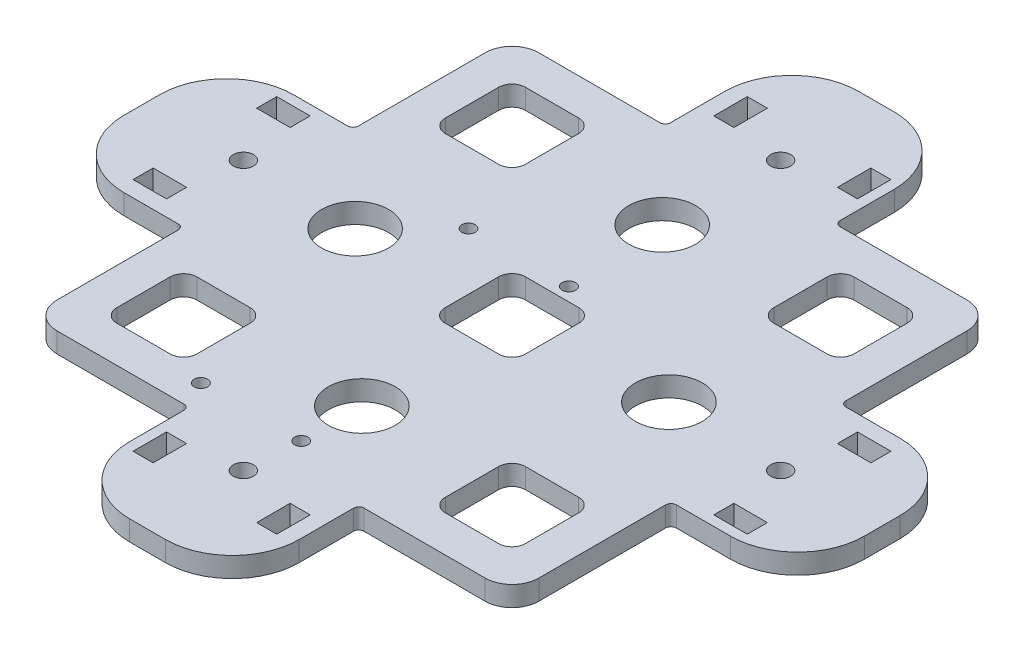
SolidWorks part; units mm, degrees
ref_plane "Front Plane" through (0, 0, 0) normal (0, 0, 1) x (1, 0, 0)
ref_plane "Top Plane" through (0, 0, 0) normal (0, 1, 0) x (1, 0, 0)
ref_plane "Right Plane" through (0, 0, 0) normal (1, 0, 0) x (0, 0, -1)
sketch "Sketch1" plane through (0, 0, 0) normal (0, 1, 0) x (1, 0, 0)
  line L0 (0, 35) -> (0, 46.25) construction
  line L1 (5.25, 23.75) -> (-5.25, 23.75) construction
  line L2 (6.1, 24.6) -> (6.1, 45.4) construction
  line L3 (5.25, 46.25) -> (-5.25, 46.25) construction
  line L4 (-6.1, 24.6) -> (-6.1, 45.4) construction
  line L5 (0, 35) -> (-6.1, 35) construction
  line L6 (36.7954, -12.2377) -> (44.9, -12.2377)
  line L7 (12.5118, 15.9935) -> (-11.6882, 15.9935) construction
  line L8 (12.2377, 36.7954) -> (12.2377, 44.9)
  line L9 (2.2377, 54.9) -> (-3.1, 54.9)
  line L10 (-13.1, 36.7954) -> (-13.1, 44.9)
  line L11 (12.5118, 15.9935) -> (-13.1, 54.9) construction
  line L12 (12.2377, 54.9) -> (-11.6882, 15.9935) construction
  line L13 (15.9935, -12.5118) -> (15.9935, 11.6882) construction
  line L14 (36.7954, 13.1) -> (44.9, 13.1)
  line L15 (54.9, -2.2377) -> (54.9, 3.1)
  line L16 (24.6, -6.1) -> (45.4, -6.1) construction
  line L17 (23.75, -5.25) -> (23.75, 5.25) construction
  line L18 (24.6, 6.1) -> (45.4, 6.1) construction
  line L19 (46.25, -5.25) -> (46.25, 5.25) construction
  line L20 (-12.2377, -36.7954) -> (-12.2377, -44.9)
  line L21 (-12.5118, -15.9935) -> (11.6882, -15.9935) construction
  line L22 (13.1, -36.7954) -> (13.1, -44.9)
  line L23 (-2.2377, -54.9) -> (3.1, -54.9)
  line L24 (-6.1, -24.6) -> (-6.1, -45.4) construction
  line L25 (-5.25, -23.75) -> (5.25, -23.75) construction
  line L26 (6.1, -24.6) -> (6.1, -45.4) construction
  line L27 (-5.25, -46.25) -> (5.25, -46.25) construction
  line L28 (-36.7954, 12.2377) -> (-44.9, 12.2377)
  line L29 (-15.9935, 12.5118) -> (-15.9935, -11.6882) construction
  line L30 (-36.7954, -13.1) -> (-44.9, -13.1)
  line L31 (-54.9, 2.2377) -> (-54.9, -3.1)
  line L32 (-24.6, 6.1) -> (-45.4, 6.1) construction
  line L33 (-23.75, 5.25) -> (-23.75, -5.25) construction
  line L34 (-24.6, -6.1) -> (-45.4, -6.1) construction
  line L35 (-46.25, 5.25) -> (-46.25, -5.25) construction
  line L36 (20.5609, 18.5609) -> (28.535, 18.5609)
  line L37 (4, -6) -> (-4, -6)
  line L38 (6, -4) -> (6, 4)
  line L39 (4, 6) -> (-4, 6)
  line L40 (-6, -4) -> (-6, 4)
  line L41 (6, -6) -> (-6, 6) construction
  line L42 (6, 6) -> (-6, -6) construction
  line L43 (32, -36) -> (13.8954, -36)
  line L44 (36, -32) -> (36, -13.033)
  line L45 (32, 36) -> (13.033, 36)
  line L46 (-36, -32) -> (-36, -13.8954)
  line L47 (36, -36) -> (-36, 36) construction
  line L48 (36, 36) -> (-36, -36) construction
  line L49 (-20.5609, 18.5609) -> (-28.535, 18.5609)
  line L50 (-18.5609, 20.5609) -> (-18.5609, 28.535)
  line L51 (-20.5609, 30.535) -> (-28.535, 30.535)
  line L52 (-30.535, 20.5609) -> (-30.535, 28.535)
  line L53 (-18.5609, 18.5609) -> (-30.535, 30.535) construction
  line L54 (-18.5609, 30.535) -> (-30.535, 18.5609) construction
  line L55 (18.5609, 20.5609) -> (18.5609, 28.535)
  line L56 (20.5609, 30.535) -> (28.535, 30.535)
  line L57 (30.535, 20.5609) -> (30.535, 28.535)
  line L58 (18.5609, -20.5609) -> (18.5609, -28.535)
  line L59 (20.5609, -18.5609) -> (28.535, -18.5609)
  line L60 (30.535, -20.5609) -> (30.535, -28.535)
  line L61 (20.5609, -30.535) -> (28.535, -30.535)
  line L62 (-20.5609, -18.5609) -> (-28.535, -18.5609)
  line L63 (-18.5609, -20.5609) -> (-18.5609, -28.535)
  line L64 (-20.5609, -30.535) -> (-28.535, -30.535)
  line L65 (-30.535, -20.5609) -> (-30.535, -28.535)
  line L66 (-36, 13.033) -> (-36, 32)
  line L67 (-13.8954, 36) -> (-32, 36)
  line L68 (-13.033, -36) -> (-32, -36)
  line L69 (36, 13.8954) -> (36, 32)
  circle A0 centre (0, 48.9) radius 1 construction
  circle A1 centre (0, 21.1) radius 1 construction
  circle A2 centre (48.9, 0) radius 1 construction
  circle A3 centre (21.1, 0) radius 1 construction
  circle A4 centre (0, -48.9) radius 1 construction
  circle A5 centre (0, -21.1) radius 1 construction
  circle A6 centre (-48.9, 0) radius 1 construction
  circle A7 centre (-21.1, 0) radius 1 construction
  arc A8 (-3.1, 54.9) -> (-13.1, 44.9) centre (-3.1, 44.9) ccw
  arc A9 (12.2377, 44.9) -> (2.2377, 54.9) centre (2.2377, 44.9) ccw
  arc A10 (44.9, 13.1) -> (54.9, 3.1) centre (44.9, 3.1) cw
  arc A11 (44.9, -12.2377) -> (54.9, -2.2377) centre (44.9, -2.2377) ccw
  arc A12 (13.1, -44.9) -> (3.1, -54.9) centre (3.1, -44.9) cw
  arc A13 (-2.2377, -54.9) -> (-12.2377, -44.9) centre (-2.2377, -44.9) cw
  arc A14 (-54.9, -3.1) -> (-44.9, -13.1) centre (-44.9, -3.1) ccw
  arc A15 (-44.9, 12.2377) -> (-54.9, 2.2377) centre (-44.9, 2.2377) ccw
  arc A16 (-13.1, 17.2377) -> (-18.1, 12.2377) centre (-18.1, 17.2377) cw
  arc A17 (12.2377, 18.1) -> (17.2377, 13.1) centre (17.2377, 18.1) ccw
  arc A18 (18.1, -12.2377) -> (13.1, -17.2377) centre (18.1, -17.2377) ccw
  arc A19 (-12.2377, -18.1) -> (-17.2377, -13.1) centre (-17.2377, -18.1) ccw
  arc A20 (-4, -6) -> (-6, -4) centre (-4, -4) cw
  arc A21 (4, -6) -> (6, -4) centre (4, -4) ccw
  arc A22 (6, 4) -> (4, 6) centre (4, 4) ccw
  arc A23 (-4, 6) -> (-6, 4) centre (-4, 4) ccw
  arc A24 (-5.25, 23.75) -> (-6.1, 24.6) centre (-5.25, 24.6) cw construction
  arc A25 (5.25, 23.75) -> (6.1, 24.6) centre (5.25, 24.6) ccw construction
  arc A26 (6.1, 45.4) -> (5.25, 46.25) centre (5.25, 45.4) ccw construction
  arc A27 (-5.25, 46.25) -> (-6.1, 45.4) centre (-5.25, 45.4) ccw construction
  arc A28 (6.1, -45.4) -> (5.25, -46.25) centre (5.25, -45.4) cw construction
  arc A29 (-6.1, -45.4) -> (-5.25, -46.25) centre (-5.25, -45.4) ccw construction
  arc A30 (-6.1, -24.6) -> (-5.25, -23.75) centre (-5.25, -24.6) cw construction
  arc A31 (5.25, -23.75) -> (6.1, -24.6) centre (5.25, -24.6) cw construction
  arc A32 (45.4, -6.1) -> (46.25, -5.25) centre (45.4, -5.25) ccw construction
  arc A33 (45.4, 6.1) -> (46.25, 5.25) centre (45.4, 5.25) cw construction
  arc A34 (23.75, 5.25) -> (24.6, 6.1) centre (24.6, 5.25) cw construction
  arc A35 (24.6, -6.1) -> (23.75, -5.25) centre (24.6, -5.25) cw construction
  arc A36 (-45.4, -6.1) -> (-46.25, -5.25) centre (-45.4, -5.25) cw construction
  arc A37 (-23.75, -5.25) -> (-24.6, -6.1) centre (-24.6, -5.25) cw construction
  arc A38 (-24.6, 6.1) -> (-23.75, 5.25) centre (-24.6, 5.25) cw construction
  arc A39 (-45.4, 6.1) -> (-46.25, 5.25) centre (-45.4, 5.25) ccw construction
  circle A40 centre (40.15, 0) radius 1.5
  circle A41 centre (0, -40.15) radius 1.5
  circle A42 centre (-40.15, 0) radius 1.5
  circle A43 centre (0, 40.15) radius 1.5
  arc A44 (-18.5609, 28.535) -> (-20.5609, 30.535) centre (-20.5609, 28.535) ccw
  arc A45 (-20.5609, 18.5609) -> (-18.5609, 20.5609) centre (-20.5609, 20.5609) ccw
  arc A46 (-28.535, 18.5609) -> (-30.535, 20.5609) centre (-28.535, 20.5609) cw
  arc A47 (-28.535, 30.535) -> (-30.535, 28.535) centre (-28.535, 28.535) ccw
  arc A48 (-20.5609, -18.5609) -> (-18.5609, -20.5609) centre (-20.5609, -20.5609) cw
  arc A49 (-28.535, -18.5609) -> (-30.535, -20.5609) centre (-28.535, -20.5609) ccw
  arc A50 (-28.535, -30.535) -> (-30.535, -28.535) centre (-28.535, -28.535) cw
  arc A51 (-18.5609, -28.535) -> (-20.5609, -30.535) centre (-20.5609, -28.535) cw
  arc A52 (18.5609, -28.535) -> (20.5609, -30.535) centre (20.5609, -28.535) ccw
  arc A53 (30.535, -28.535) -> (28.535, -30.535) centre (28.535, -28.535) cw
  arc A54 (18.5609, -20.5609) -> (20.5609, -18.5609) centre (20.5609, -20.5609) cw
  arc A55 (28.535, -18.5609) -> (30.535, -20.5609) centre (28.535, -20.5609) cw
  arc A56 (28.535, 30.535) -> (30.535, 28.535) centre (28.535, 28.535) cw
  arc A57 (28.535, 18.5609) -> (30.535, 20.5609) centre (28.535, 20.5609) ccw
  arc A58 (20.5609, 18.5609) -> (18.5609, 20.5609) centre (20.5609, 20.5609) cw
  arc A59 (18.5609, 28.535) -> (20.5609, 30.535) centre (20.5609, 28.535) cw
  arc A60 (-36, -32) -> (-32, -36) centre (-32, -32) ccw
  arc A61 (32, -36) -> (36, -32) centre (32, -32) ccw
  arc A62 (32, 36) -> (36, 32) centre (32, 32) cw
  arc A63 (-36, 32) -> (-32, 36) centre (-32, 32) cw
  arc A64 (-12.2377, -36.7954) -> (-13.033, -36) centre (-13.033, -36.7954) ccw
  arc A65 (13.1, -36.7954) -> (13.8954, -36) centre (13.8954, -36.7954) cw
  arc A66 (36, -13.033) -> (36.7954, -12.2377) centre (36.7954, -13.033) cw
  arc A67 (36.7954, 13.1) -> (36, 13.8954) centre (36.7954, 13.8954) cw
  arc A68 (13.033, 36) -> (12.2377, 36.7954) centre (13.033, 36.7954) cw
  arc A69 (-13.1, 36.7954) -> (-13.8954, 36) centre (-13.8954, 36.7954) cw
  arc A70 (-36.7954, 12.2377) -> (-36, 13.033) centre (-36.7954, 13.033) ccw
  arc A71 (-36, -13.8954) -> (-36.7954, -13.1) centre (-36.7954, -13.8954) ccw
  point P0 (0, 35)
  point P82 (0, 0)
  point P133 (0, 0)
  point P144 (-24.548, 24.548)
  dimension "D1" = 2
  dimension "D5" = 10
  dimension "D6" = 5
  dimension "D8" = 2
  dimension "D9" = 0.85
  dimension "D10" = 0.85
  dimension "D11" = 3
  dimension "D15" = 2
  dimension "D16" = 2
  dimension "D17" = 4
  dimension "D18" = 0.7954
  dimension "D2" = 27.8
  dimension "D3" = 7
  dimension "D4" = 6
  dimension "D7" = 12
  dimension "D12" = 16.4
  dimension "D13" = 72
  dimension "D14" = 5.465
extrude "Boss-Extrude1" add sketch "Sketch1" along normal blind 3 contours A19 L20 A13 L23 A12 L22 A18 L6 A11 L15 A10 L14 A17 L8 A9 L9 A8 L10 A16 L28 A15 L31 A14 L30 A43 A42 A41 A40 A23 L39 A22 L38 A21 L37 A20 L40 | A63 L66 L28 A16 L10 L67 A47 L51 A44 L50 A45 L49 A46 L52 | A62 L45 L8 A17 L14 L69 L55 A59 L56 A56 L57 A57 L36 A58 | L43 A61 L44 L6 A18 L22 L59 A55 L60 A53 L61 A52 L58 A54 | L46 A60 L68 L20 A19 L30 L63 A51 L64 A50 L65 A49 L62 A48
sketch "Sketch2" plane through (0, 3, 0) normal (0, 1, 0) x (1, 0, 0)
  line L0 (-14.5, -12) -> (0.5, -12) construction
  line L1 (32.5, -35) -> (-32.5, -35) construction
  line L2 (32.5, -35) -> (32.5, 35) construction
  line L3 (32.5, 35) -> (-32.5, 35) construction
  line L4 (-32.5, -35) -> (-32.5, 35) construction
  line L5 (32.5, -35) -> (-32.5, 35) construction
  line L6 (32.5, 35) -> (-32.5, -35) construction
  line L7 (-14.5, -32) -> (0.5, -32) construction
  line L8 (-14.5, -32) -> (-14.5, 8) construction
  line L9 (-14.5, 8) -> (0.5, 8) construction
  line L10 (0.5, -32) -> (0.5, 8) construction
  line L11 (-7, -32) -> (-7, -12) construction
  line L13 (-36, -32) -> (-36, -13.8954) construction
  circle A0 centre (-14.5, -32) radius 1
  circle A1 centre (0.5, -32) radius 1
  circle A2 centre (-14.5, 8) radius 1
  circle A3 centre (0.5, 8) radius 1
  circle A4 centre (0.5, -22.9477) radius 5
  circle A5 centre (-22.9477, -0.5) radius 5
  circle A6 centre (-0.5, 22.9477) radius 5
  circle A7 centre (22.9477, 0.5) radius 5
  point P0 (0, 0)
  point P25 (-36, -22.9477)
  dimension "D7" = 2
  dimension "D8" = 10
  dimension "D1" = 70
  dimension "D2" = 65
  dimension "D3" = 18
  dimension "D4" = 40
  dimension "D5" = 3
  dimension "D6" = 15
  dimension "D9" = 4
extrude "Cut-Extrude1" cut sketch "Sketch2" against normal up to surface (3 mm away) up to face at (0, 0, 0)
sketch "Sketch3" plane through (0, 3, 0) normal (0, 1, 0) x (1, 0, 0)
  line L0 (-54.9, 2.2377) -> (-54.9, -3.1) construction
  line L1 (-45.9, 7.7377) -> (-40.9, 7.7377)
  line L2 (-45.9, 7.7377) -> (-45.9, 10.7377)
  line L3 (-45.9, 10.7377) -> (-40.9, 10.7377)
  line L4 (-40.9, 7.7377) -> (-40.9, 10.7377)
  line L5 (-36.7954, 12.2377) -> (-44.9, 12.2377) construction
  line L6 (-38.65, 0) -> (-6, 0) construction
  line L7 (-6, -4) -> (-6, 4) construction
  line L8 (-45.9, -10.7377) -> (-40.9, -10.7377)
  line L9 (-40.9, -7.7377) -> (-40.9, -10.7377)
  line L10 (-45.9, -7.7377) -> (-40.9, -7.7377)
  line L11 (-45.9, -7.7377) -> (-45.9, -10.7377)
  line L12 (7.7377, 45.9) -> (10.7377, 45.9)
  line L13 (7.7377, 45.9) -> (7.7377, 40.9)
  line L14 (7.7377, 40.9) -> (10.7377, 40.9)
  line L15 (10.7377, 45.9) -> (10.7377, 40.9)
  line L16 (-10.7377, 45.9) -> (-10.7377, 40.9)
  line L17 (-7.7377, 40.9) -> (-10.7377, 40.9)
  line L18 (-7.7377, 45.9) -> (-7.7377, 40.9)
  line L19 (-7.7377, 45.9) -> (-10.7377, 45.9)
  line L20 (45.9, -7.7377) -> (45.9, -10.7377)
  line L21 (45.9, -7.7377) -> (40.9, -7.7377)
  line L22 (40.9, -7.7377) -> (40.9, -10.7377)
  line L23 (45.9, -10.7377) -> (40.9, -10.7377)
  line L24 (45.9, 10.7377) -> (40.9, 10.7377)
  line L25 (40.9, 7.7377) -> (40.9, 10.7377)
  line L26 (45.9, 7.7377) -> (40.9, 7.7377)
  line L27 (45.9, 7.7377) -> (45.9, 10.7377)
  line L28 (-7.7377, -45.9) -> (-10.7377, -45.9)
  line L29 (-7.7377, -45.9) -> (-7.7377, -40.9)
  line L30 (-7.7377, -40.9) -> (-10.7377, -40.9)
  line L31 (-10.7377, -45.9) -> (-10.7377, -40.9)
  line L32 (10.7377, -45.9) -> (10.7377, -40.9)
  line L33 (7.7377, -40.9) -> (10.7377, -40.9)
  line L34 (7.7377, -45.9) -> (7.7377, -40.9)
  line L35 (7.7377, -45.9) -> (10.7377, -45.9)
  circle A0 centre (-40.15, 0) radius 1.5 construction
  point P8 (-40.8477, 12.2377)
  dimension "D1" = 3
  dimension "D2" = 9
  dimension "D3" = 5
  dimension "D4" = 1.5
  dimension "D5" = 4
extrude "Cut-Extrude3" cut sketch "Sketch3" against normal up to surface (3 mm away) up to face at (0.5, 0, 27.9477)
